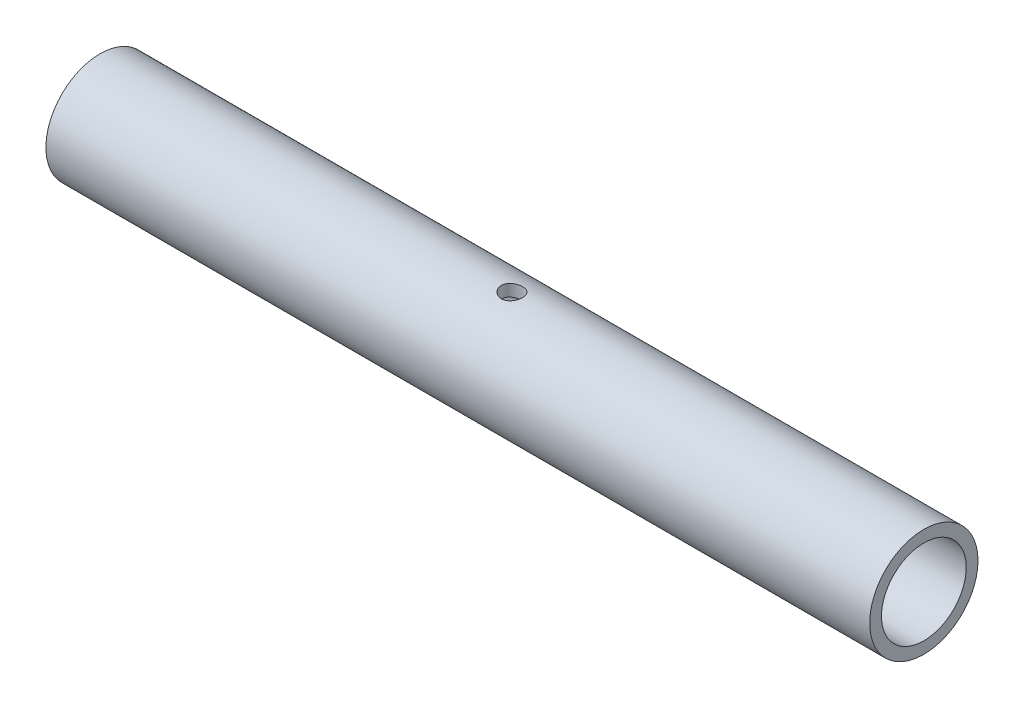
SolidWorks part; units mm, degrees
ref_plane "Front Plane" through (0, 0, 0) normal (0, 0, 1) x (1, 0, 0)
ref_plane "Top Plane" through (0, 0, 0) normal (0, 1, 0) x (1, 0, 0)
ref_plane "Right Plane" through (0, 0, 0) normal (1, 0, 0) x (0, 0, -1)
sketch "Sketch1" plane through (0, 0, 0) normal (1, 0, 0) x (0, 0, -1)
  circle A0 centre (0, 0) radius 16.7005
  circle A1 centre (0, 0) radius 13.0683
  dimension "D1" = 33.401
  dimension "D2" = 26.1366
extrude "Boss-Extrude1" add sketch "Sketch1" along normal blind 254
sketch "Sketch2" plane through (0, 0, 0) normal (0, 0, 1) x (1, 0, 0)
  line L0 (0, 0) -> (25.4, 0) construction
  line L1 (0, 16.7005) -> (0, -16.7005) construction
  line L2 (127, 16.7005) -> (127, -16.7005) construction
  line L3 (254, 16.7005) -> (0, 16.7005) construction
  line L4 (0, -16.7005) -> (254, -16.7005) construction
  line L5 (254, 0) -> (228.6, 0) construction
  circle A0 centre (25.4, 0) radius 3.2639
  circle A1 centre (228.6, 0) radius 3.2639
  dimension "D1" = 6.5278
  dimension "D2" = 25.4
extrude "Cut-Extrude1" [suppressed] cut sketch "Sketch2" against normal through all both and the other way through all
sketch "Sketch3" plane through (0, 0, 0) normal (0, 1, 0) x (1, 0, 0)
  line L0 (127, 16.7005) -> (127, -16.7005) construction
  line L1 (254, 16.7005) -> (0, 16.7005) construction
  line L2 (0, -16.7005) -> (254, -16.7005) construction
  circle A0 centre (127, 0) radius 3.2639
  dimension "D1" = 6.5278
extrude "Cut-Extrude2" cut sketch "Sketch3" against normal through all both and the other way through all
